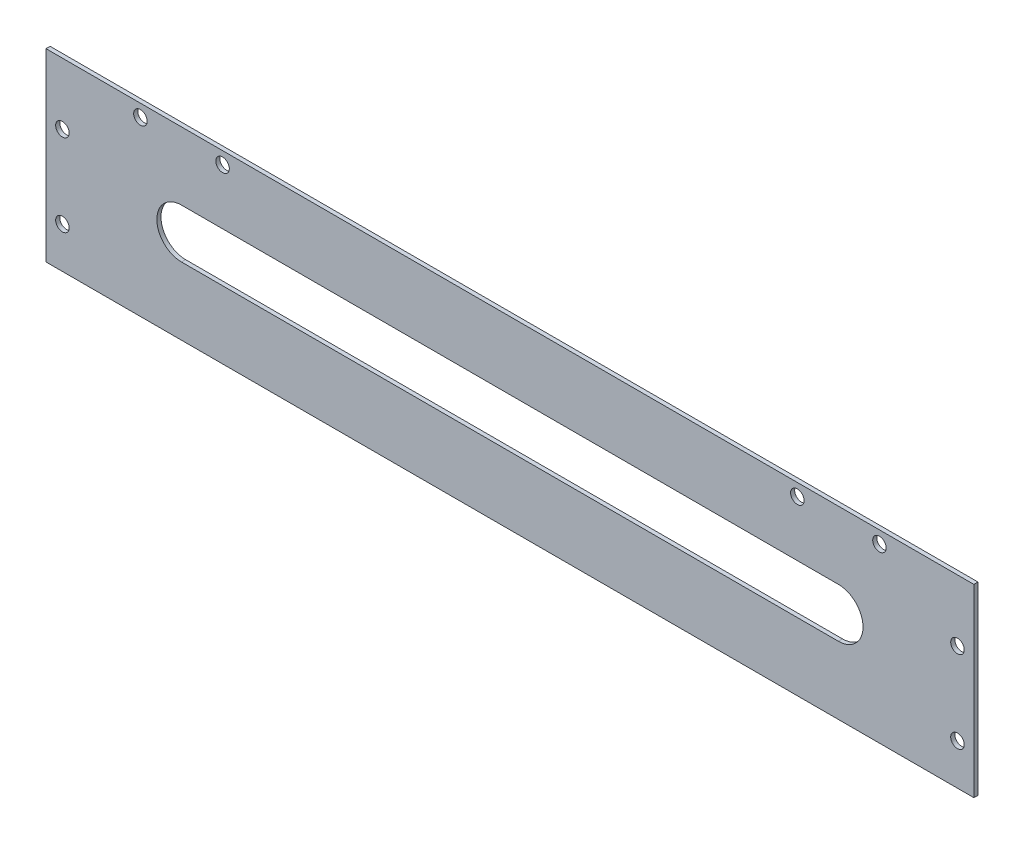
SolidWorks part; units mm, degrees
material "环氧板"
ref_plane "前视基准面" through (0, 0, 0) normal (0, 0, 1) x (1, 0, 0)
ref_plane "上视基准面" through (0, 0, 0) normal (0, 1, 0) x (1, 0, 0)
ref_plane "右视基准面" through (0, 0, 0) normal (1, 0, 0) x (0, 0, -1)
other "Configuration Table"
sketch "草图1" plane through (0, 0, 0) normal (0, 0, 1) x (1, 0, 0)
  line L1 (-113, 22.5) -> (113, 22.5)
  line L2 (-113, 22.5) -> (-113, -22.5)
  line L3 (-113, -22.5) -> (113, -22.5)
  line L4 (113, 22.5) -> (113, -22.5)
  line L5 (-113, 22.5) -> (113, -22.5) construction
  line L6 (-113, -22.5) -> (113, 22.5) construction
  point P0 (0, 0)
  dimension "D1" = 226
  dimension "40" = 45
extrude "凸台-拉伸1" add sketch "草图1" along normal blind 1
sketch "草图2" plane through (0, 0, 1) normal (0, 0, 1) x (1, 0, 0)
  line L1 (113, 22.5) -> (-113, 22.5) construction
  line L2 (0, 22.5) -> (0, -31.9375) construction
  circle A0 centre (90, 19.5) radius 1.65
  circle A1 centre (70, 19.5) radius 1.65
  circle A2 centre (-70, 19.5) radius 1.65
  circle A3 centre (-90, 19.5) radius 1.65
  dimension "D2" = 3
  dimension "D3" = 20
  dimension "D4" = 3.3
  dimension "D1" = 140
extrude "切除-拉伸1" cut sketch "草图2" against normal through all
sketch "草图3" plane through (0, 0, 1) normal (0, 0, 1) x (1, 0, 0)
  line L3 (-80, 0) -> (80, 0) construction
  line L4 (-80, 6) -> (80, 6)
  line L5 (-80, -6) -> (80, -6)
  arc A0 (-80, 6) -> (-80, -6) centre (-80, 0) ccw
  arc A1 (80, -6) -> (80, 6) centre (80, 0) ccw
  point P2 (0, 0)
  dimension "D1" = 6
  dimension "D2" = 160
extrude "切除-拉伸2" cut sketch "草图3" against normal blind 10
sketch "草图4" plane through (0, 0, 1) normal (0, 0, 1) x (1, 0, 0)
  line L0 (113, 22.5) -> (-113, 22.5) construction
  line L1 (113, -22.5) -> (113, 22.5) construction
  line L2 (0, 22.5) -> (0, -48.9915) construction
  circle A0 centre (109, 7.5) radius 1.65
  circle A1 centre (109, -12.5) radius 1.65
  circle A2 centre (-109, -12.5) radius 1.65
  circle A3 centre (-109, 7.5) radius 1.65
  dimension "D1" = 20
  dimension "D2" = 15
  dimension "D3" = 3.3
  dimension "D4" = 4
extrude "切除-拉伸3" cut sketch "草图4" against normal through all
